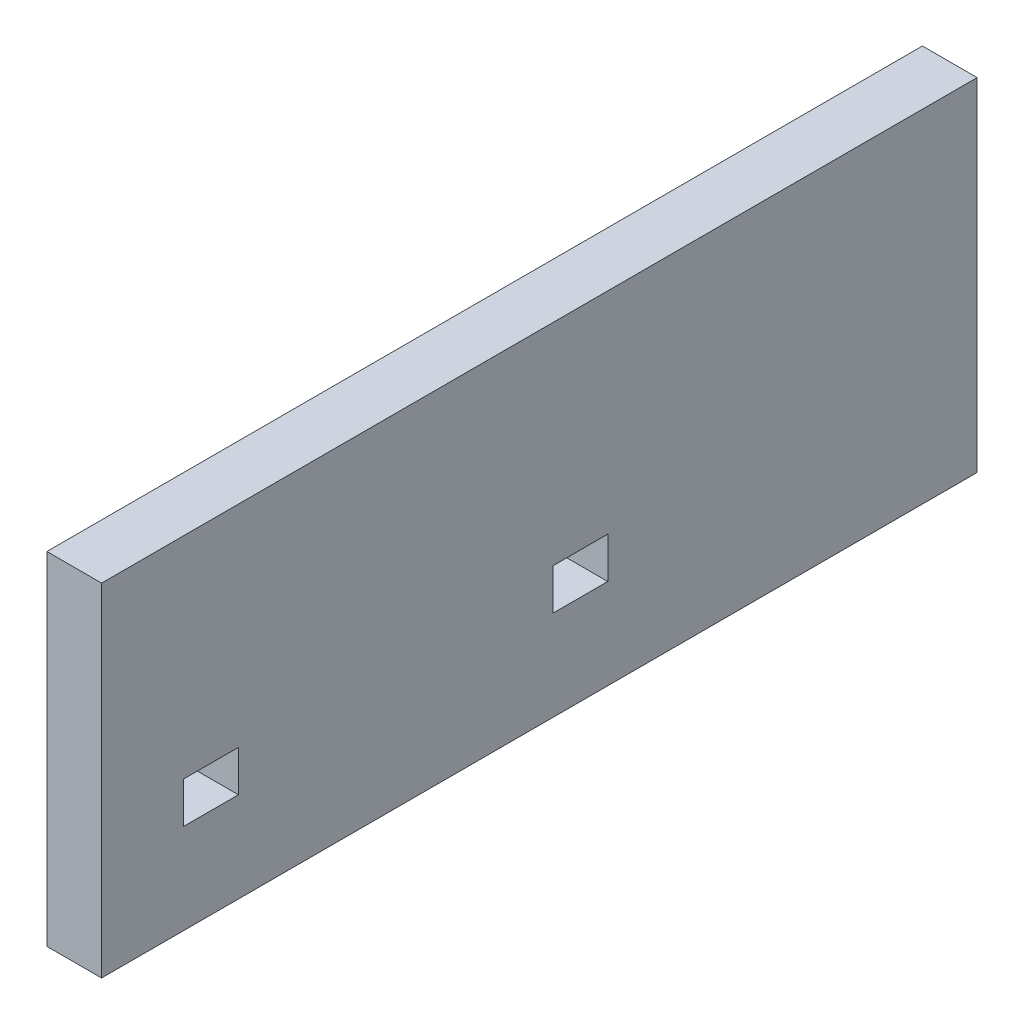
SolidWorks part; units mm, degrees
ref_plane "Front Plane" through (0, 0, 0) normal (0, 0, 1) x (1, 0, 0)
ref_plane "Top Plane" through (0, 0, 0) normal (0, 1, 0) x (1, 0, 0)
ref_plane "Right Plane" through (0, 0, 0) normal (1, 0, 0) x (0, 0, -1)
sketch "Sketch1" plane through (0, 0, 0) normal (1, 0, 0) x (0, 0, -1)
  line L1 (-26.4878, 12.0122) -> (37.5122, 12.0122)
  line L2 (-26.4878, 12.0122) -> (-26.4878, -12.9878)
  line L3 (-26.4878, -12.9878) -> (37.5122, -12.9878)
  line L4 (37.5122, 12.0122) -> (37.5122, -12.9878)
  dimension "D1" = 64
  dimension "D2" = 25
extrude "Boss-Extrude1" add sketch "Sketch1" along normal blind 4
sketch "Sketch2" plane through (0, 0, 0) normal (-1, 0, 0) x (0, 0, 1)
  line L0 (26.4878, -12.9878) -> (-37.5122, -12.9878) construction
  line L1 (16.4878, -3.3878) -> (20.4878, -3.3878)
  line L2 (16.4878, -3.3878) -> (16.4878, -6.3878)
  line L3 (16.4878, -6.3878) -> (20.4878, -6.3878)
  line L4 (20.4878, -3.3878) -> (20.4878, -6.3878)
  line L5 (26.4878, 12.0122) -> (26.4878, -12.9878) construction
  dimension "D1" = 4
  dimension "D2" = 3
  dimension "D3" = 6.6
  dimension "D4" = 6
extrude "Cut-Extrude1" cut sketch "Sketch2" against normal blind 6.54
sketch "Sketch3" plane through (0, 0, 0) normal (-1, 0, 0) x (0, 0, 1)
  line L0 (26.4878, -12.9878) -> (-37.5122, -12.9878) construction
  line L1 (-10.5122, -3.3878) -> (-6.5122, -3.3878)
  line L2 (-10.5122, -3.3878) -> (-10.5122, -6.3878)
  line L3 (-10.5122, -6.3878) -> (-6.5122, -6.3878)
  line L4 (-6.5122, -3.3878) -> (-6.5122, -6.3878)
  line L5 (26.4878, 12.0122) -> (26.4878, -12.9878) construction
  dimension "D1" = 4
  dimension "D2" = 3
  dimension "D3" = 6.6
  dimension "D4" = 33
extrude "Cut-Extrude2" cut sketch "Sketch3" against normal blind 6.54
sketch "Sketch6" plane through (0, 0, 0) normal (-1, 0, 0) x (0, 0, 1)
  line L0 (-10.5122, -3.3878) -> (-10.5122, -6.3878) construction
  text T0 "LED1" font "Arial Rounded MT Bold" height 1
  dimension "D1" = 0
extrude "Boss-Extrude3" add sketch "Sketch6" along normal blind 0.4
sketch "Sketch7" plane through (0, 0, 0) normal (-1, 0, 0) x (0, 0, 1)
  text T0 "LED2" font "Arial Rounded MT Bold" height 1
extrude "Boss-Extrude4" add sketch "Sketch7" along normal blind 0.4
